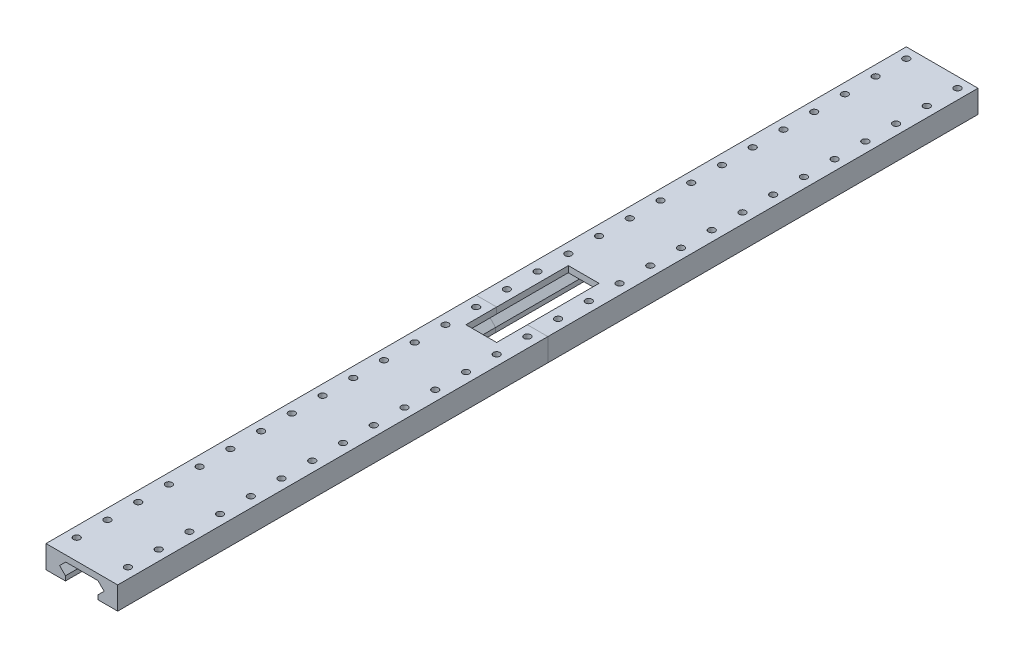
SolidWorks part; units mm, degrees
ref_plane "前视基准面" through (0, 0, 0) normal (0, 0, 1) x (1, 0, 0)
ref_plane "上视基准面" through (0, 0, 0) normal (0, 1, 0) x (1, 0, 0)
ref_plane "右视基准面" through (0, 0, 0) normal (1, 0, 0) x (0, 0, -1)
other "Configuration Table"
sketch "草图1" plane through (0, 0, 0) normal (0, 0, 1) x (1, 0, 0)
  line L0 (0, 0) -> (0, -50000) construction
  line L1 (0, 0) -> (-50000, 0) construction
  line L2 (10, 0) -> (-10, 0)
  line L3 (-10, 0) -> (-10, 2)
  line L4 (-10, 2) -> (-9.3, 2)
  line L5 (-7.8, 3.5) -> (-7.8, 5.8)
  line L6 (-7.8, 5.8) -> (-10.6, 8.6)
  line L7 (-10.6, 8.6) -> (-7.8, 11.4)
  line L8 (-7.8, 11.4) -> (7.8, 11.4)
  line L9 (10.6, 8.6) -> (7.8, 11.4)
  line L10 (7.8, 5.8) -> (10.6, 8.6)
  line L11 (7.8, 3.5) -> (7.8, 5.8)
  line L12 (10, 2) -> (9.3, 2)
  line L13 (10, 0) -> (10, 2)
  line L14 (8, 3.5) -> (8, 5.7172)
  line L15 (8, 5.7172) -> (10.8828, 8.6)
  line L16 (10.8828, 8.6) -> (7.8828, 11.6)
  line L17 (-7.8828, 11.6) -> (7.8828, 11.6)
  line L18 (-10.8828, 8.6) -> (-7.8828, 11.6)
  line L19 (-8, 5.7172) -> (-10.8828, 8.6)
  line L20 (-8, 3.5) -> (-8, 5.7172)
  line L21 (-10.2, 2.2) -> (-9.3, 2.2)
  line L22 (-10.2, -0.2) -> (-10.2, 2.2)
  line L23 (10.2, -0.2) -> (-10.2, -0.2)
  line L24 (10.2, -0.2) -> (10.2, 2.2)
  line L25 (10.2, 2.2) -> (9.3, 2.2)
  line L26 (-8, 3.5) -> (-17.5, 3.5)
  line L27 (-17.5, 3.5) -> (-17.5, 14.6)
  line L28 (-17.5, 14.6) -> (17.5, 14.6)
  line L29 (8, 3.5) -> (17.5, 3.5)
  line L30 (17.5, 3.5) -> (17.5, 14.6)
  arc A0 (-9.3, 2) -> (-7.8, 3.5) centre (-9.3, 3.5) ccw
  arc A1 (9.3, 2) -> (7.8, 3.5) centre (9.3, 3.5) cw
  arc A2 (9.3, 2.2) -> (8, 3.5) centre (9.3, 3.5) cw
  arc A3 (-9.3, 2.2) -> (-8, 3.5) centre (-9.3, 3.5) ccw
  point P21 (0, 11.4)
  point P25 (0, 0)
  point P43 (0, 14.6)
  dimension "D7" = 1.5
  dimension "D1" = 45
  dimension "D2" = 21.2
  dimension "D3" = 15.6
  dimension "D4" = 9.4
  dimension "D5" = 2
  dimension "D6" = 20
  dimension "D9" = 35
  dimension "D10" = 3
  dimension "D8" = 0.2
ref_plane "基准面1" through (0, 0, -150) normal (0, 0, 1) x (1, 0, 0)
sketch "草图2" plane through (0, 0, -150) normal (0, 0, 1) x (1, 0, 0)
  line L0 (-120, 0) -> (-120, -50000) construction
  line L2 (0, 200000) -> (0, -250000) construction
  line L3 (-120, 40) -> (49880, 40) construction
  line L4 (200000, 0) -> (-250000, 0) construction
  point P8 (-120, 40)
  dimension "D1" = 120
  dimension "D2" = 40
sketch3d "3D草图1"
  line L0 (-120, 40, -150) -> (0, 0, 0)
extrude "凸台-拉伸2" add sketch "草图1" along normal blind 420 contours L29 L30 L28 L27 L26 L20 L19 L18 L17 L16 L15 L14
sketch "草图3" plane through (0, 14.6, 0) normal (0, 1, 0) x (1, 0, 0)
  line L0 (0, 0) -> (0, -50000) construction
  line L1 (-12.5, -5) -> (-12.5, -20) construction
  line L2 (-17.5, -420) -> (-17.5, 0) construction
  line L3 (-17.5, 0) -> (17.5, 0) construction
  circle A0 centre (-12.5, -5) radius 1.6
  circle A1 centre (-12.5, -20) radius 1.6
  circle A2 centre (-12.5, -35) radius 1.6
  circle A3 centre (-12.5, -50) radius 1.6
  circle A4 centre (-12.5, -65) radius 1.6
  circle A5 centre (-12.5, -80) radius 1.6
  circle A6 centre (-12.5, -95) radius 1.6
  circle A7 centre (-12.5, -110) radius 1.6
  circle A8 centre (-12.5, -125) radius 1.6
  circle A9 centre (-12.5, -140) radius 1.6
  circle A10 centre (-12.5, -155) radius 1.6
  circle A11 centre (-12.5, -170) radius 1.6
  circle A12 centre (-12.5, -185) radius 1.6
  circle A13 centre (-12.5, -200) radius 1.6
  circle A14 centre (-12.5, -215) radius 1.6
  circle A15 centre (-12.5, -230) radius 1.6
  circle A16 centre (-12.5, -245) radius 1.6
  circle A17 centre (-12.5, -260) radius 1.6
  circle A18 centre (-12.5, -275) radius 1.6
  circle A19 centre (-12.5, -290) radius 1.6
  circle A20 centre (-12.5, -305) radius 1.6
  circle A21 centre (-12.5, -320) radius 1.6
  circle A22 centre (-12.5, -335) radius 1.6
  circle A23 centre (-12.5, -350) radius 1.6
  circle A24 centre (-12.5, -365) radius 1.6
  circle A25 centre (-12.5, -380) radius 1.6
  circle A26 centre (-12.5, -395) radius 1.6
  circle A27 centre (-12.5, -410) radius 1.6
  circle A28 centre (12.5, -410) radius 1.6
  circle A29 centre (12.5, -395) radius 1.6
  circle A30 centre (12.5, -380) radius 1.6
  circle A31 centre (12.5, -365) radius 1.6
  circle A32 centre (12.5, -350) radius 1.6
  circle A33 centre (12.5, -335) radius 1.6
  circle A34 centre (12.5, -320) radius 1.6
  circle A35 centre (12.5, -305) radius 1.6
  circle A36 centre (12.5, -290) radius 1.6
  circle A37 centre (12.5, -275) radius 1.6
  circle A38 centre (12.5, -260) radius 1.6
  circle A39 centre (12.5, -245) radius 1.6
  circle A40 centre (12.5, -230) radius 1.6
  circle A41 centre (12.5, -215) radius 1.6
  circle A42 centre (12.5, -200) radius 1.6
  circle A43 centre (12.5, -185) radius 1.6
  circle A44 centre (12.5, -170) radius 1.6
  circle A45 centre (12.5, -155) radius 1.6
  circle A46 centre (12.5, -140) radius 1.6
  circle A47 centre (12.5, -125) radius 1.6
  circle A48 centre (12.5, -110) radius 1.6
  circle A49 centre (12.5, -95) radius 1.6
  circle A50 centre (12.5, -80) radius 1.6
  circle A51 centre (12.5, -65) radius 1.6
  circle A52 centre (12.5, -50) radius 1.6
  circle A53 centre (12.5, -35) radius 1.6
  circle A54 centre (12.5, -20) radius 1.6
  circle A55 centre (12.5, -5) radius 1.6
  dimension "D3" = 3.2
  dimension "D4" = 5
  dimension "D5" = 5
  dimension "D2" = 15
  dimension "D1" = 28
extrude "切除-拉伸1" cut sketch "草图3" against normal through all
sketch "草图4" plane through (0, 14.6, 0) normal (0, 1, 0) x (1, 0, 0)
  line L0 (0, 0) -> (0, -50000) construction
  line L1 (-17.5, 0) -> (17.5, 0) construction
  line L2 (-7.5, -175) -> (7.5, -175)
  line L3 (-7.5, -175) -> (-7.5, -225)
  line L4 (-7.5, -225) -> (7.5, -225)
  line L5 (7.5, -175) -> (7.5, -225)
  line L6 (-7.5, -175) -> (7.5, -225) construction
  line L7 (-7.5, -225) -> (7.5, -175) construction
  point P3 (0, -200)
  dimension "D1" = 15
  dimension "D2" = 175
  dimension "D3" = 50
extrude "切除-拉伸2" cut sketch "草图4" against normal through all
sketch "草图5" [suppressed] plane through (0, 14.6, 0) normal (0, 1, 0) x (1, 0, 0)
  line L0 (17.5, -420) -> (17.5, 0) construction
  line L1 (-17.5, 0) -> (17.5, 0)
  line L2 (-17.5, 0) -> (-17.5, -210)
  line L3 (-17.5, -210) -> (17.5, -210)
  line L4 (17.5, 0) -> (17.5, -210)
  line L6 (-17.5, -420) -> (17.5, -420)
  line L7 (-17.5, -420) -> (-17.5, -210)
  line L8 (-17.5, -210) -> (17.5, -210)
  line L9 (17.5, -420) -> (17.5, -210)
  dimension "D1" = 210
extrude "切除-拉伸3" [suppressed] cut sketch "草图5" against normal through all contours L4 L1 L2 L3
sketch "草图6" [suppressed] plane through (0, 14.6, 0) normal (0, 1, 0) x (1, 0, 0)
  line L0 (17.5, -420) -> (17.5, 0) construction
  line L1 (-17.5, -420) -> (17.5, -420)
  line L2 (-17.5, -420) -> (-17.5, -210)
  line L3 (-17.5, -210) -> (17.5, -210)
  line L4 (17.5, -420) -> (17.5, -210)
  dimension "D1" = 210
extrude "切除-拉伸4" [suppressed] cut sketch "草图6" against normal through all
ref_plane "基准面2" through (0, 0, 210) normal (0, 0, -1) x (-1, 0, 0)
split "分割1" trim tools "基准面2" bodies to split 110 resulting bodies 114 115
